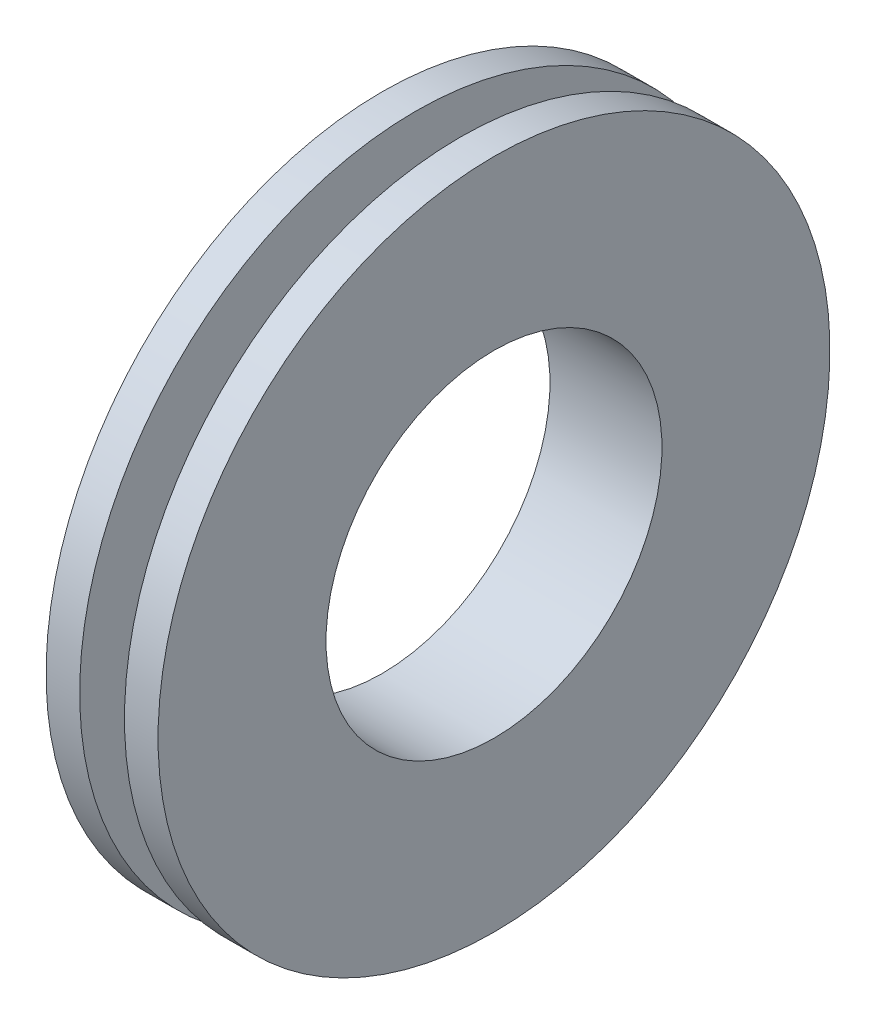
SolidWorks part; units mm, degrees
ref_plane "Front Plane" through (0, 0, 0) normal (0, 0, 1) x (1, 0, 0)
ref_plane "Top Plane" through (0, 0, 0) normal (0, 1, 0) x (1, 0, 0)
ref_plane "Right Plane" through (0, 0, 0) normal (1, 0, 0) x (0, 0, -1)
sketch "Sketch2" plane through (0, 0, 0) normal (0, 0, 1) x (1, 0, 0)
  line L0 (0, 0) -> (-27.1519, 0) construction
  line L1 (0, 15) -> (-10, 15)
  line L2 (-10, 15) -> (-10, 30)
  line L3 (-10, 30) -> (-7, 30)
  line L4 (-7, 30) -> (-7, 22)
  line L5 (-7, 22) -> (-3, 22)
  line L6 (-3, 22) -> (-3, 30)
  line L7 (-3, 30) -> (0, 30)
  line L8 (0, 30) -> (0, 15)
  dimension "D1" = 15
  dimension "D2" = 15
  dimension "D3" = 15
  dimension "D4" = 8
  dimension "D5" = 3
  dimension "D6" = 3
  dimension "D7" = 10
revolve "Revolve1" add sketch "Sketch2" angle 360 about L0
sketch "Sketch3" plane through (0, 0, 0) normal (1, 0, 0) x (0, 0, -1)
  point P0 (-27.2549, -4.3534)
